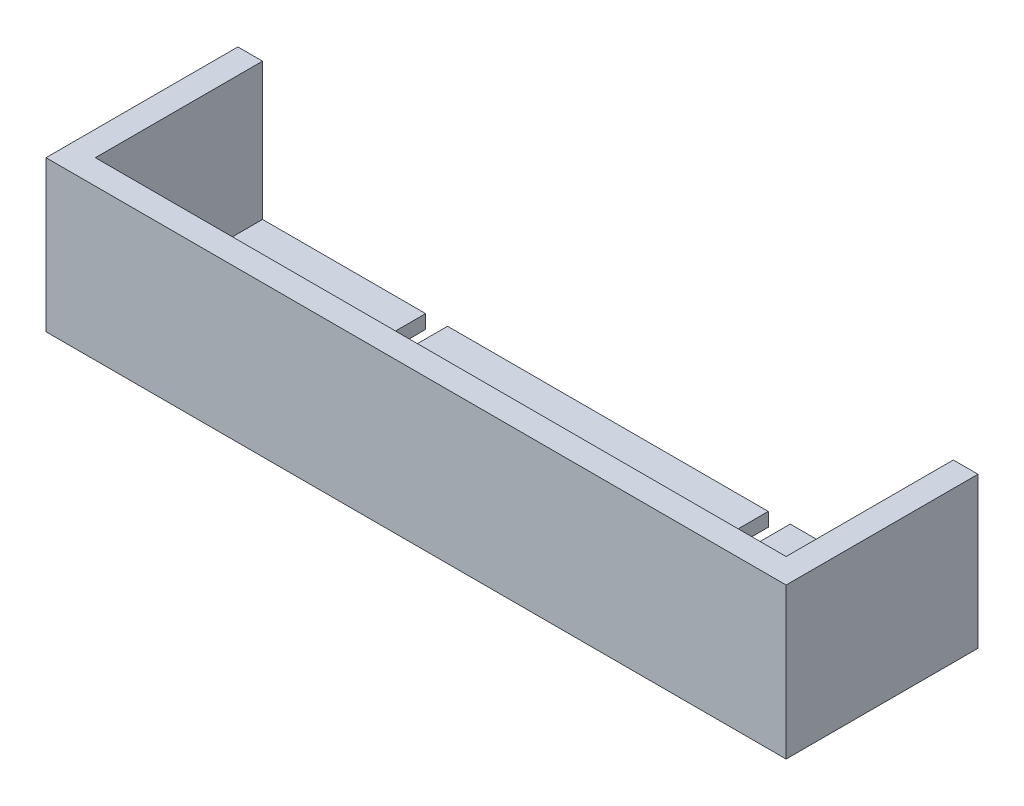
SolidWorks part; units mm, degrees
ref_plane "Plan de face" through (0, 0, 0) normal (0, 0, 1) x (1, 0, 0)
ref_plane "Plan de dessus" through (0, 0, 0) normal (0, 1, 0) x (1, 0, 0)
ref_plane "Plan de droite" through (0, 0, 0) normal (1, 0, 0) x (0, 0, -1)
sketch "Esquisse1" plane through (0, 0, 0) normal (0, 1, 0) x (1, 0, 0)
  line L1 (-27, 7) -> (27, 7)
  line L2 (-27, 7) -> (-27, -7)
  line L3 (-27, -7) -> (27, -7)
  line L4 (27, 7) -> (27, -7)
  line L5 (-25.2, 5.2) -> (25.2, 5.2)
  line L6 (-25.2, 5.2) -> (-25.2, -5.2)
  line L7 (-25.2, -5.2) -> (25.2, -5.2)
  line L8 (25.2, 5.2) -> (25.2, -5.2)
  dimension "D1" = 54
  dimension "D2" = 14
  dimension "D3" = 7
  dimension "D4" = 27
  dimension "D5" = 1.8
  dimension "D6" = 1.8
  dimension "D7" = 1.8
  dimension "D8" = 1.8
extrude "Boss.-Extru.1" add sketch "Esquisse1" along normal blind 10
sketch "Esquisse2" plane through (0, 0, 0) normal (0, -1, 0) x (-1, 0, 0)
  line L1 (27, -7) -> (-27, -7)
  line L2 (27, -7) -> (27, 7)
  line L3 (27, 7) -> (-27, 7)
  line L4 (-27, -7) -> (-27, 7)
extrude "Boss.-Extru.2" add sketch "Esquisse2" along normal blind 1
sketch "Esquisse3" plane through (0, 0, 0) normal (0, 1, 0) x (1, 0, 0)
  line L0 (27, 7) -> (-27, 7) construction
  line L2 (-13.3, 0) -> (-13.3, 7)
  line L3 (-13.3, 7) -> (-11.7, 7)
  line L4 (-11.7, 0) -> (-11.7, 7)
  line L7 (11.7, 0) -> (11.7, 7)
  line L8 (11.7, 7) -> (13.3, 7)
  line L9 (13.3, 0) -> (13.3, 7)
  arc A0 (-13.3, 0) -> (-11.7, 0) centre (-12.5, 0) ccw
  arc A1 (11.7, 0) -> (13.3, 0) centre (12.5, 0) ccw
  dimension "D1" = 1.6
  dimension "D2" = 1.6
  dimension "D3" = 12.5
  dimension "D4" = 12.5
extrude "Enlèv. mat.-Extru.1" cut sketch "Esquisse3" against normal blind 1
sketch "Esquisse4" plane through (0, 0, -5.2) normal (0, 0, 1) x (1, 0, 0)
  line L1 (-25.2, 0) -> (25.2, 0)
  line L2 (-25.2, 0) -> (-25.2, 10)
  line L3 (-25.2, 10) -> (25.2, 10)
  line L4 (25.2, 0) -> (25.2, 10)
extrude "Enlèv. mat.-Extru.2" cut sketch "Esquisse4" against normal up to surface (1.8 mm away) up to face at (0, 1.1667, -7)
